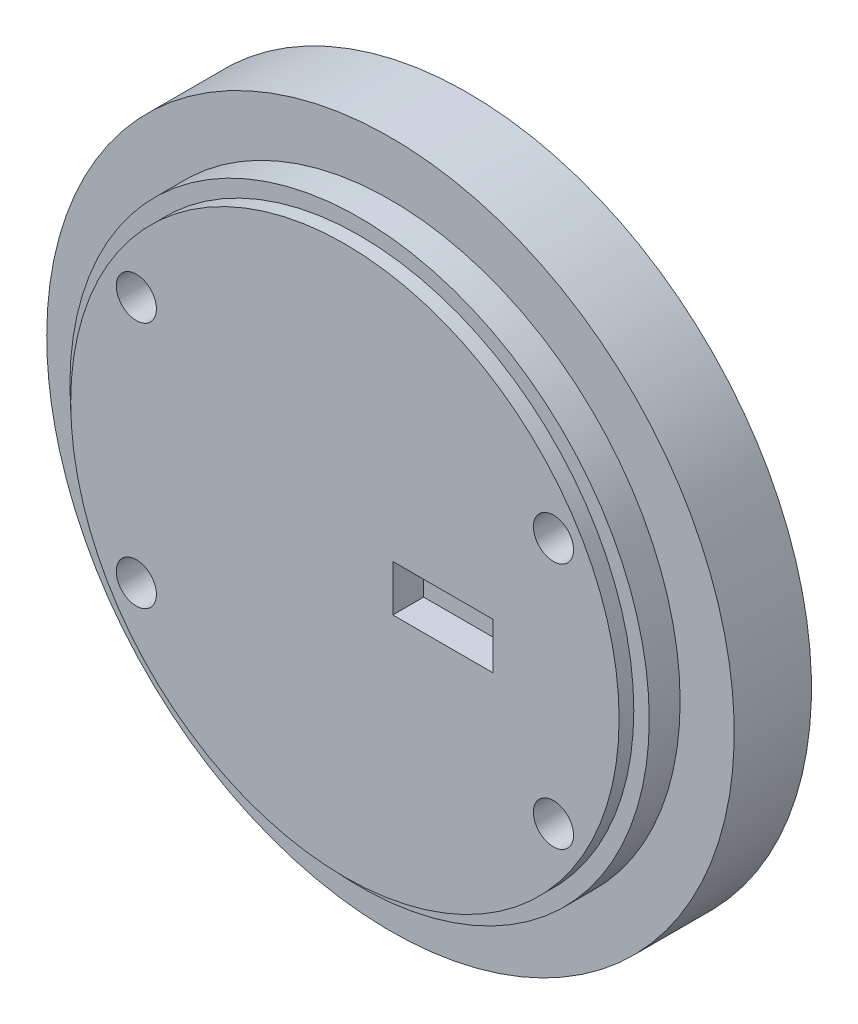
SolidWorks part; units mm, degrees
ref_plane "前视基准面" through (0, 0, 0) normal (0, 0, 1) x (1, 0, 0)
ref_plane "上视基准面" through (0, 0, 0) normal (0, 1, 0) x (1, 0, 0)
ref_plane "右视基准面" through (0, 0, 0) normal (1, 0, 0) x (0, 0, -1)
other "Configuration Table"
sketch "草图1" plane through (0, 0, 0) normal (0, 0, 1) x (1, 0, 0)
  line L0 (0, 0) -> (0, 52.1137) construction
  line L1 (0, 0) -> (55.2559, 0) construction
  line L2 (-27, 0) -> (-27, 16) construction
  line L3 (-27, 16) -> (0, 16) construction
  circle A0 centre (0, 0) radius 35.5
  circle A1 centre (-27, 16) radius 2.6
  circle A2 centre (-27, -16) radius 2.6
  circle A3 centre (27, -16) radius 2.6
  circle A4 centre (27, 16) radius 2.6
  dimension "D1" = 71
  dimension "D4" = 5.2
  dimension "D2" = 27
  dimension "D3" = 16
extrude "凸台-拉伸2" add sketch "草图1" along normal blind 1.9
sketch "草图2" plane through (0, 0, 1.9) normal (0, 0, 1) x (1, 0, 0)
  line L0 (0, 0) -> (12.7, 0) construction
  line L2 (19.2, -3) -> (6.2, -3)
  line L3 (19.2, -3) -> (19.2, 3)
  line L4 (19.2, 3) -> (6.2, 3)
  line L5 (6.2, -3) -> (6.2, 3)
  line L6 (19.2, -3) -> (6.2, 3) construction
  line L7 (19.2, 3) -> (6.2, -3) construction
  dimension "D1" = 12.7
  dimension "D2" = 13
  dimension "D3" = 6
sketch "草图3" plane through (0, 0, 0) normal (0, 0, -1) x (-1, 0, 0)
  circle A0 centre (0, 0) radius 37.5
  circle A1 centre (27, 16) radius 2.6 construction
  circle A2 centre (27, -16) radius 2.6 construction
  circle A3 centre (-27, -16) radius 2.6 construction
  circle A4 centre (-27, 16) radius 2.6 construction
  circle A5 centre (27, 16) radius 2.6
  circle A6 centre (27, -16) radius 2.6
  circle A7 centre (-27, -16) radius 2.6
  circle A8 centre (-27, 16) radius 2.6
  dimension "D1" = 75
extrude "凸台-拉伸3" add sketch "草图3" along normal blind 4
extrude "切除-拉伸6" cut sketch "草图2" against normal blind 4 contours L4 L5 L2 L3
sketch "草图4" plane through (0, 0, -4) normal (0, 0, -1) x (-1, 0, 0)
  line L0 (0, 0) -> (25.4854, 0) construction
  line L1 (0, 0) -> (0, 15.7246) construction
  circle A0 centre (0, 0) radius 44.5
  circle A1 centre (0, 0) radius 40.5 construction
  circle A14 centre (0, 40.5) radius 2
  circle A15 centre (35.074, 20.25) radius 2
  circle A16 centre (35.074, -20.25) radius 2
  circle A17 centre (0, -40.5) radius 2
  circle A18 centre (-35.074, -20.25) radius 2
  circle A19 centre (-35.074, 20.25) radius 2
  point P24 (0, 0)
  point P25 (-2, 0.0026)
  point P26 (0, 0)
  dimension "D1" = 89
  dimension "D2" = 81
  dimension "D3" = 6
  dimension "D4" = 4
extrude "凸台-拉伸4" add sketch "草图4" along normal blind 10
sketch "草图7" plane through (0, 0, 1.9) normal (0, 0, 1) x (1, 0, 0)
  circle A0 centre (27, -16) radius 2.6 construction
  circle A1 centre (27, 16) radius 2.6 construction
  circle A2 centre (-27, -16) radius 2.6 construction
  circle A3 centre (-27, 16) radius 2.6 construction
  circle A4 centre (27, -16) radius 2.6
  circle A5 centre (27, 16) radius 2.6
  circle A6 centre (-27, -16) radius 2.6
  circle A7 centre (-27, 16) radius 2.6
extrude "切除-拉伸7" cut sketch "草图7" against normal through all
sketch "草图10" plane through (0, 0, -14) normal (0, 0, -1) x (-1, 0, 0)
  line L0 (0, 0) -> (0, 17.6698) construction
  line L1 (0, 0) -> (14.0169, 0) construction
  circle A0 centre (-27, 16) radius 5
  circle A1 centre (27, 16) radius 5
  circle A2 centre (27, -16) radius 5
  circle A3 centre (-27, -16) radius 5
  dimension "D1" = 10
extrude "切除-拉伸8" cut sketch "草图10" against normal blind 6.18
sketch "草图12" plane through (0, 0, -4) normal (0, 0, 1) x (1, 0, 0)
  circle A0 centre (35.074, -20.25) radius 2 construction
  circle A1 centre (35.074, 20.25) radius 2 construction
  circle A2 centre (0, 40.5) radius 2 construction
  circle A3 centre (-35.074, 20.25) radius 2 construction
  circle A4 centre (-35.074, -20.25) radius 2 construction
  circle A5 centre (0, -40.5) radius 2 construction
  circle A6 centre (35.074, -20.25) radius 2
  circle A7 centre (35.074, 20.25) radius 2
  circle A8 centre (0, 40.5) radius 2
  circle A9 centre (-35.074, 20.25) radius 2
  circle A10 centre (-35.074, -20.25) radius 2
  circle A11 centre (0, -40.5) radius 2
extrude "凸台-拉伸6" add sketch "草图12" against normal blind 2
sketch "草图13" plane through (0, 0, -14) normal (0, 0, -1) x (-1, 0, 0)
  line L0 (8.1911, 0) -> (23.4832, 0) construction
  line L1 (0, 0) -> (0, 12.0457) construction
  line L8 (12, -42.8515) -> (12, -47.7911) construction
  line L9 (12, -27.8515) -> (12, -42.8515) construction
  line L10 (-12, -27.8515) -> (12, -27.8515) construction
  line L11 (-12, -47.7911) -> (-12, -42.8515) construction
  line L12 (-12, -42.8515) -> (-12, -27.8515) construction
  line L13 (12, -47.7911) -> (-12, -47.7911) construction
  line L16 (-36.07, 0) -> (-36.07, 12) construction
  line L28 (47.5342, -12) -> (42.8515, -12)
  line L29 (36.07, -12) -> (42.8515, -12)
  line L30 (36.07, -12) -> (31.57, -12)
  line L31 (31.57, -12) -> (31.57, -10)
  line L32 (31.57, -10) -> (28.3618, -10)
  line L33 (28.3618, -10) -> (28.3618, 10)
  line L34 (31.57, 10) -> (28.3618, 10)
  line L35 (31.57, 12) -> (31.57, 10)
  line L36 (36.07, 12) -> (31.57, 12)
  line L37 (36.07, 12) -> (42.8515, 12)
  line L38 (42.8515, 12) -> (47.5342, 12)
  line L39 (47.5342, 12) -> (47.5342, -12)
  point P21 (-28.3618, 0)
  point P22 (0, 0)
  dimension "D1" = 24
  dimension "D2" = 12
  dimension "D3" = 15
extrude "切除-拉伸9" cut sketch "草图13" against normal blind 2.5
